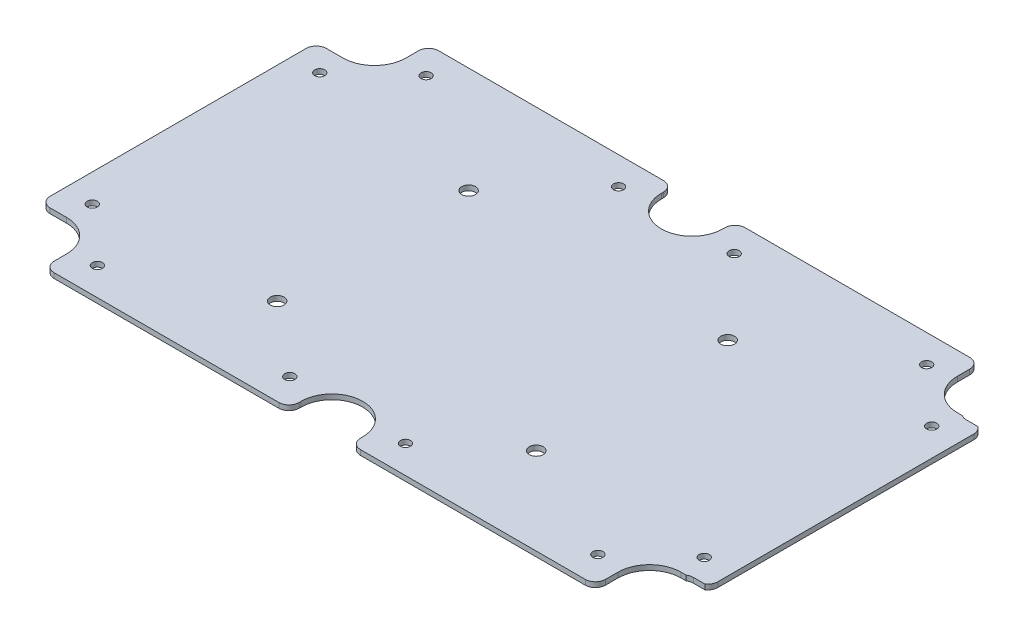
SolidWorks part; units mm, degrees
ref_plane "Front Plane" through (0, 0, 0) normal (0, 0, 1) x (1, 0, 0)
ref_plane "Top Plane" through (0, 0, 0) normal (0, 1, 0) x (1, 0, 0)
ref_plane "Right Plane" through (0, 0, 0) normal (1, 0, 0) x (0, 0, -1)
ref_plane "Plane1" through (0, 9.652, 0) normal (0, -1, 0) x (1, 0, 0)
sketch "Sketch1" plane through (0, 9.652, 0) normal (0, -1, 0) x (1, 0, 0)
  line L0 (-9.6495, -57.089) -> (-9.6495, -56.4515)
  line L1 (9.6495, -56.4515) -> (9.6495, -57.089)
  line L2 (12.8245, -60.264) -> (83.2283, -60.264)
  line L3 (86.4033, -57.089) -> (86.4033, -53.1978)
  line L4 (96.3068, -43.2943) -> (97.9048, -43.2943)
  line L5 (99.642, -42.7769) -> (103.2127, -42.7769)
  line L6 (104.6505, -40.1193) -> (104.6505, 40.1193)
  line L7 (103.2127, 42.7769) -> (99.642, 42.7769)
  line L8 (97.9048, 43.2943) -> (96.3068, 43.2943)
  line L9 (86.4033, 53.1978) -> (86.4033, 57.089)
  line L10 (83.2283, 60.264) -> (12.8245, 60.264)
  line L11 (9.6495, 57.089) -> (9.6495, 56.4515)
  line L12 (-9.6495, 56.4515) -> (-9.6495, 57.089)
  line L13 (-12.8245, 60.264) -> (-83.2283, 60.264)
  line L14 (-86.4033, 57.089) -> (-86.4033, 53.1978)
  line L15 (-96.3068, 43.2943) -> (-101.4755, 43.2943)
  line L16 (-104.6505, 40.1193) -> (-104.6505, -40.1193)
  line L17 (-101.4755, -43.2943) -> (-96.3068, -43.2943)
  line L18 (-86.4033, -53.1978) -> (-86.4033, -57.089)
  line L19 (-83.2283, -60.264) -> (-12.8245, -60.264)
  circle A0 centre (18.1292, 51.5303) radius 1.5875
  circle A1 centre (18.1292, -51.5303) radius 1.5875
  circle A2 centre (95.9167, -35.6553) radius 1.5875
  circle A3 centre (78.4543, 51.5303) radius 1.5875
  circle A4 centre (-95.9167, 35.6553) radius 1.5875
  circle A5 centre (-78.4543, -51.5303) radius 1.5875
  circle A6 centre (-18.1292, -51.5303) radius 1.5875
  circle A7 centre (-95.9167, -35.6553) radius 1.5875
  circle A8 centre (-78.4543, 51.5303) radius 1.5875
  circle A9 centre (95.9167, 35.6553) radius 1.5875
  circle A10 centre (78.4543, -51.5303) radius 1.5875
  circle A11 centre (-18.1292, 51.5303) radius 1.5875
  arc A12 (-12.8245, -60.264) -> (-9.6495, -57.089) centre (-12.8245, -57.089) ccw
  arc A13 (-9.6495, -56.4515) -> (9.6495, -56.4515) centre (0, -56.4515) cw
  arc A14 (9.6495, -57.089) -> (12.8245, -60.264) centre (12.8245, -57.089) ccw
  arc A15 (83.2283, -60.264) -> (86.4033, -57.089) centre (83.2283, -57.089) ccw
  arc A16 (86.4033, -53.1978) -> (96.3068, -43.2943) centre (96.3068, -53.1978) cw
  arc A17 (97.9048, -43.2943) -> (99.642, -42.7769) centre (99.642, -45.9519) cw
  arc A18 (103.2127, -42.7769) -> (104.6505, -40.1193) centre (101.4755, -40.1193) ccw
  arc A19 (104.6505, 40.1193) -> (103.2127, 42.7769) centre (101.4755, 40.1193) ccw
  arc A20 (99.642, 42.7769) -> (97.9048, 43.2943) centre (99.642, 45.9519) cw
  arc A21 (96.3068, 43.2943) -> (86.4033, 53.1978) centre (96.3068, 53.1978) cw
  arc A22 (86.4033, 57.089) -> (83.2283, 60.264) centre (83.2283, 57.089) ccw
  arc A23 (12.8245, 60.264) -> (9.6495, 57.089) centre (12.8245, 57.089) ccw
  arc A24 (9.6495, 56.4515) -> (-9.6495, 56.4515) centre (0, 56.4515) cw
  arc A25 (-9.6495, 57.089) -> (-12.8245, 60.264) centre (-12.8245, 57.089) ccw
  arc A26 (-83.2283, 60.264) -> (-86.4033, 57.089) centre (-83.2283, 57.089) ccw
  arc A27 (-86.4033, 53.1978) -> (-96.3068, 43.2943) centre (-96.3068, 53.1978) cw
  arc A28 (-101.4755, 43.2943) -> (-104.6505, 40.1193) centre (-101.4755, 40.1193) ccw
  arc A29 (-104.6505, -40.1193) -> (-101.4755, -43.2943) centre (-101.4755, -40.1193) ccw
  arc A30 (-96.3068, -43.2943) -> (-86.4033, -53.1978) centre (-96.3068, -53.1978) cw
  arc A31 (-86.4033, -57.089) -> (-83.2283, -60.264) centre (-83.2283, -57.089) ccw
extrude "Boss-Extrude1" add sketch "Sketch1" against normal blind 1.5875
sketch "Sketch2" plane through (0, 11.2395, 0) normal (0, 1, 0) x (1, 0, 0)
  line L1 (-40.605, -33) -> (-40.605, 27)
  line L2 (-40.605, 27) -> (40.605, 27)
  line L3 (40.605, 27) -> (40.605, -33)
  line L4 (40.605, -33) -> (-40.605, -33)
  circle A0 centre (-40.605, 27) radius 2.16
  circle A1 centre (-40.605, -33) radius 2.16
  circle A2 centre (40.605, -33) radius 2.16
  circle A3 centre (40.605, 27) radius 2.16
  point P6 (-40.605, -3)
  dimension "D4" = 4.32
  dimension "D5" = 4.32
  dimension "D6" = 4.32
  dimension "D7" = 4.32
  dimension "D1" = 40.605
  dimension "D2" = 60
  dimension "D3" = 81.21
  dimension "D8" = 27
extrude "Cut-Extrude1" cut sketch "Sketch2" against normal blind 10 contours L2 A0 L1 | L1 A0 L2 | L1 A1 L4 | L4 A1 L1 | L4 A2 L3 | L3 A2 L4 | L3 A3 L2 | L2 A3 L3
